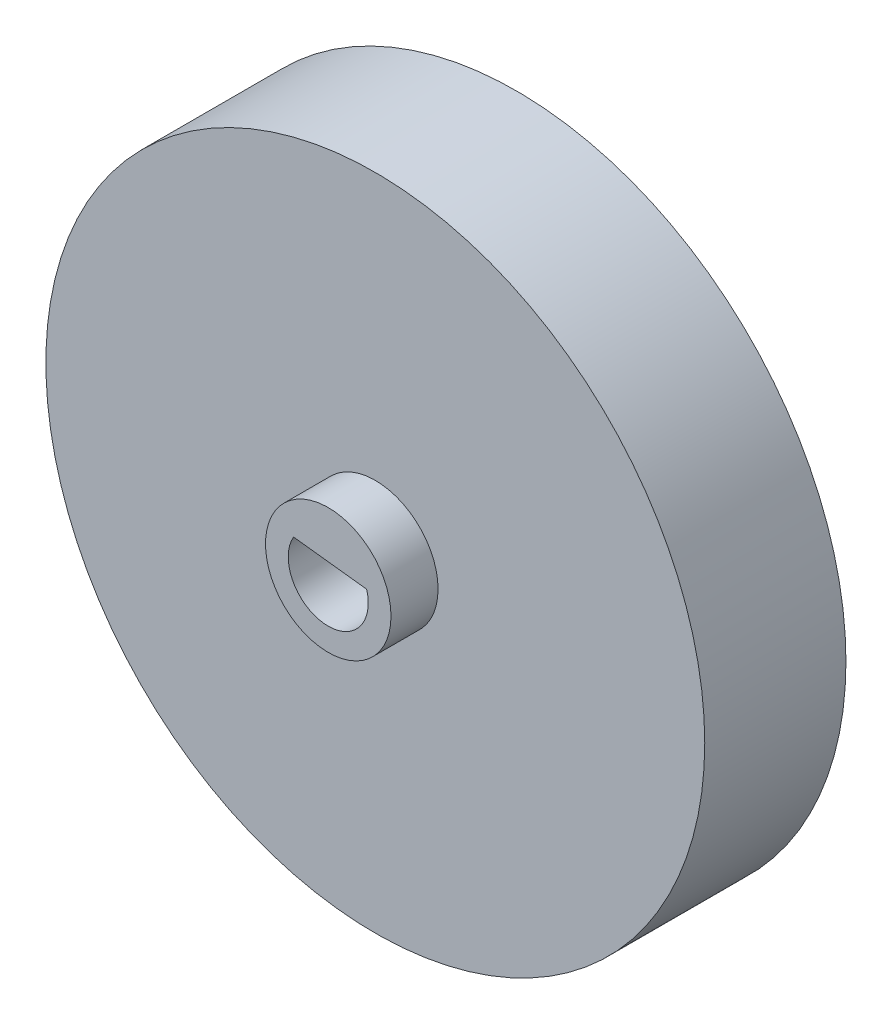
SolidWorks part; units mm, degrees
ref_plane "前视基准面" through (0, 0, 0) normal (0, 0, 1) x (1, 0, 0)
ref_plane "上视基准面" through (0, 0, 0) normal (0, 1, 0) x (1, 0, 0)
ref_plane "右视基准面" through (0, 0, 0) normal (1, 0, 0) x (0, 0, -1)
other "Configuration Table"
sketch "草图1" plane through (0, 0, 0) normal (0, 0, 1) x (1, 0, 0)
  line L0 (4.894, 1.4347) -> (-4.4239, 2.5376)
  circle A0 centre (0, 0) radius 8
  arc A1 (-4.4239, 2.5376) -> (4.894, 1.4347) centre (0, 0) ccw
extrude "凸台-拉伸1" add sketch "草图1" along normal blind 24
sketch "草图2" plane through (0, 0, 0) normal (0, 0, 1) x (1, 0, 0)
  circle A0 centre (0, 0) radius 42
  circle A1 centre (0, 0) radius 8
extrude "凸台-拉伸2" add sketch "草图2" along normal blind 18
sketch "草图3" plane through (0, 0, 0) normal (0, 0, 1) x (1, 0, 0)
  arc A0 (37.5326, -2.0353) -> (37.5326, 2.0353) centre (0, 0) ccw
  arc A1 (41.987, 1.0447) -> (41.987, -1.0447) centre (0, 0) cw
  spline S0 degree 4 poles (0.0375, -3) (0.0375, -3.0013) (0.0374, -3.0071) (0.0364, -3.02) (0.0345, -3.0352) (0.0319, -3.0515) (0.0291, -3.0657) (0.0272, -3.0752) (0.0246, -3.0866) (0.0213, -3.1003) (0.0171, -3.1164) (0.0119, -3.1346) (0.0061, -3.1531) (0.0001, -3.1713) (-0.0065, -3.1897) (-0.0131, -3.2075) (-0.0204, -3.2259) (-0.0274, -3.2431) (-0.0356, -3.262) (-0.0425, -3.2776) (-0.0539, -3.302) (-0.059, -3.3124) (-0.0668, -3.3281) (-0.0696, -3.3334) knots 0 0 0 0 0 0.015084 0.064855 0.146842 0.174209 0.201575 0.228941 0.256307 0.307035 0.361767 0.4165 0.471232 0.525964 0.580697 0.635429 0.690161 0.744894 0.799626 0.854358 0.909091 1 1 1 1 1 construction
  spline S1 degree 4 poles (0.0375, -3) (0.0375, -3.0013) (0.0374, -3.0071) (0.0364, -3.02) (0.0345, -3.0352) (0.0319, -3.0515) (0.0291, -3.0657) (0.0272, -3.0752) (0.0246, -3.0866) (0.0213, -3.1003) (0.0171, -3.1164) (0.0119, -3.1346) (0.0061, -3.1531) (0.0001, -3.1713) (-0.0065, -3.1897) (-0.0131, -3.2075) (-0.0204, -3.2259) (-0.0274, -3.2431) (-0.0356, -3.262) (-0.0425, -3.2776) (-0.0498, -3.2933) (-0.0536, -3.3011) (-0.0555, -3.3051) knots 0 0 0 0 0 0.015084 0.064855 0.146842 0.174209 0.201575 0.228941 0.256307 0.307035 0.361767 0.4165 0.471232 0.525964 0.580697 0.635429 0.690161 0.744894 0.799626 0.854358 0.909091 0.909091 0.909091 0.909091 0.909091
  spline S2 degree 4 poles (-0.0696, -3.3307) (-0.0669, -3.3255) (-0.059, -3.3099) (-0.0539, -3.2996) (-0.0425, -3.2755) (-0.0355, -3.26) (-0.0273, -3.2413) (-0.0203, -3.2243) (-0.013, -3.206) (-0.0064, -3.1884) (0.0001, -3.1701) (0.0062, -3.1521) (0.0119, -3.1337) (0.0171, -3.1157) (0.0213, -3.0998) (0.0246, -3.0862) (0.0282, -3.0702) (0.0318, -3.0522) (0.0348, -3.0336) (0.0368, -3.016) (0.0374, -3.0054) (0.0375, -3.0013) (0.0375, -3) knots 0 0 0 0 0 0.090909 0.1456 0.20029 0.254981 0.309672 0.364362 0.419053 0.473744 0.528434 0.583125 0.637815 0.692506 0.742942 0.770287 0.797632 0.879668 0.953111 0.984933 1 1 1 1 1 construction
  spline S3 degree 4 poles (-0.0555, -3.3027) (-0.0536, -3.2988) (-0.0498, -3.291) (-0.0425, -3.2755) (-0.0355, -3.26) (-0.0273, -3.2413) (-0.0203, -3.2243) (-0.013, -3.206) (-0.0064, -3.1884) (0.0001, -3.1701) (0.0062, -3.1521) (0.0119, -3.1337) (0.0171, -3.1157) (0.0213, -3.0998) (0.0246, -3.0862) (0.0282, -3.0702) (0.0318, -3.0522) (0.0348, -3.0336) (0.0368, -3.016) (0.0374, -3.0054) (0.0375, -3.0013) (0.0375, -3) knots 0.090909 0.090909 0.090909 0.090909 0.090909 0.1456 0.20029 0.254981 0.309672 0.364362 0.419053 0.473744 0.528434 0.583125 0.637815 0.692506 0.742942 0.770287 0.797632 0.879668 0.953111 0.984933 1 1 1 1 1
